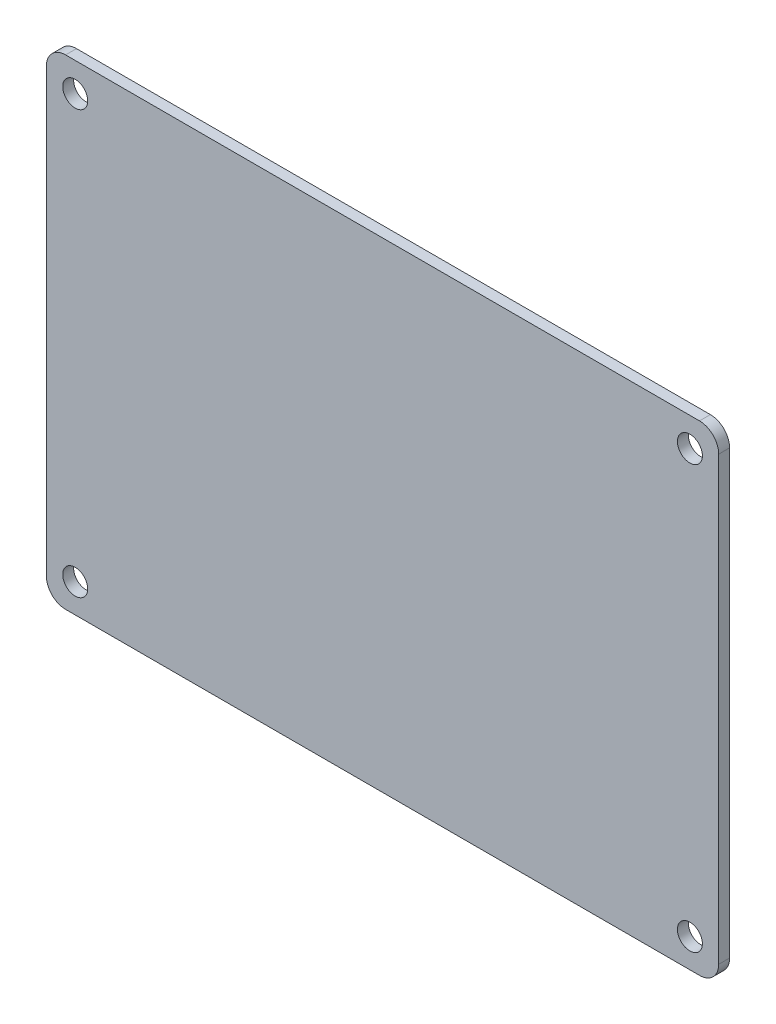
SolidWorks part; units mm, degrees
ref_plane "Plan de face" through (0, 0, 0) normal (0, 0, 1) x (1, 0, 0)
ref_plane "Plan de dessus" through (0, 0, 0) normal (0, 1, 0) x (1, 0, 0)
ref_plane "Plan de droite" through (0, 0, 0) normal (1, 0, 0) x (0, 0, -1)
sketch "Esquisse1" plane through (0, 0, 0) normal (0, 0, 1) x (1, 0, 0)
  line L1 (52.5, -37.5) -> (-52.5, -37.5)
  line L2 (52.5, -37.5) -> (52.5, 37.5)
  line L3 (52.5, 37.5) -> (-52.5, 37.5)
  line L4 (-52.5, -37.5) -> (-52.5, 37.5)
  line L5 (52.5, -37.5) -> (-52.5, 37.5) construction
  line L6 (52.5, 37.5) -> (-52.5, -37.5) construction
  point P0 (0, 0)
  dimension "D1" = 105
  dimension "D2" = 75
extrude "Boss.-Extru.1" add sketch "Esquisse1" along normal blind 1.7 contours L4 L3 L2 L1
hole_wizard "Dégagement M3.51" positions "Esquisse2" profile "Esquisse4" hole size "M3.5" standard "Ansi Metric" end condition through all
sketch "Esquisse2" plane through (0, 0, 1.7) normal (0, 0, 1) x (1, 0, 0)
  line L0 (52.5, 37.5) -> (-52.5, 37.5) construction
  line L1 (52.5, -37.5) -> (52.5, 37.5) construction
  point P0 (48, 33)
  dimension "D1" = 4.5
  dimension "D2" = 4.5
sketch "Esquisse4" plane through (48, 33, 1.7) normal (1, 0, 0) x (0, -1, 0)
  line L0 (0, 0) -> (0, 1.7)
  line L1 (0, 1.7) -> (1.95, 1.7)
  line L2 (1.95, 1.7) -> (1.95, 0)
  line L5 (1.95, 0) -> (0, 0)
  line L11 (0, -6.35) -> (0, 107.95) construction
  dimension "Diamètre du perçage jusqu'au prochain" = 3.9
  dimension "Profondeur du perçage jusqu'au prochain" = 1.7
pattern_linear "Répétition linéaire1" count 2 spacing 96 along (-1, 0, 0) count 2 spacing 66 along (0, -1, 0) of "Dégagement M3.51"
fillet "Congé1" radius 3 4 edges at (-52.5, -37.5, 0.85) (52.5, -37.5, 0.85) (52.5, 37.5, 0.85) (-52.5, 37.5, 0.85)
